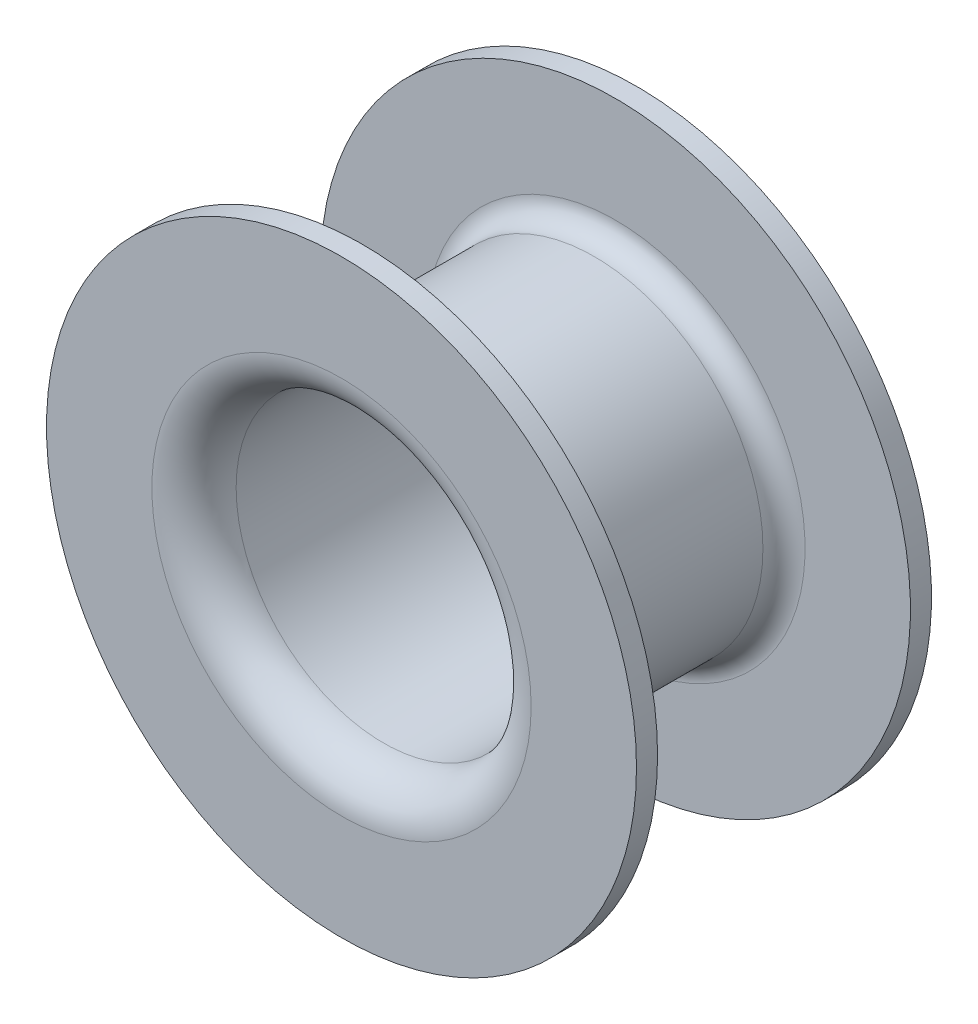
SolidWorks part; units mm, degrees
ref_plane "Спереди" through (0, 0, 0) normal (0, 0, 1) x (1, 0, 0)
ref_plane "Сверху" through (0, 0, 0) normal (0, 1, 0) x (1, 0, 0)
ref_plane "Справа" through (0, 0, 0) normal (1, 0, 0) x (0, 0, -1)
sketch "Эскиз1" plane through (0, 0, 0) normal (0, 0, 1) x (1, 0, 0)
  line L0 (-27.0435, 0) -> (28.3112, 0) construction
  circle A0 centre (0, 0) radius 3.5
  circle A1 centre (0, 0) radius 1.75
  dimension "D1" = 7
  dimension "D2" = 3.5
extrude "Вытянуть1" add sketch "Эскиз1" along normal blind 0.25
sketch "Эскиз2" plane through (0, 0, 0) normal (0, 0, -1) x (-1, 0, 0)
  circle A0 centre (0, 0) radius 1.75 construction
  circle A1 centre (0, 0) radius 1.75
  circle A2 centre (0, 0) radius 2
  dimension "D1" = 4
extrude "Вытянуть2" add sketch "Эскиз2" along normal blind 3
sketch "Эскиз3" plane through (0, 0, -3) normal (0, 0, -1) x (-1, 0, 0)
  circle A0 centre (0, 0) radius 1.75 construction
  circle A1 centre (0, 0) radius 3.5
  circle A2 centre (0, 0) radius 3.5
  circle A3 centre (0, 0) radius 1.75
  dimension "D1" = 0
extrude "Вытянуть3" add sketch "Эскиз3" along normal blind 0.25
fillet "Скругление1" radius 0.25 2 edges at (-2, 0, -3) (2, 0, 0)
fillet "Скругление2" radius 0.5 2 edges at (1.75, 0, 0.25) (-1.75, 0, -3.25)
